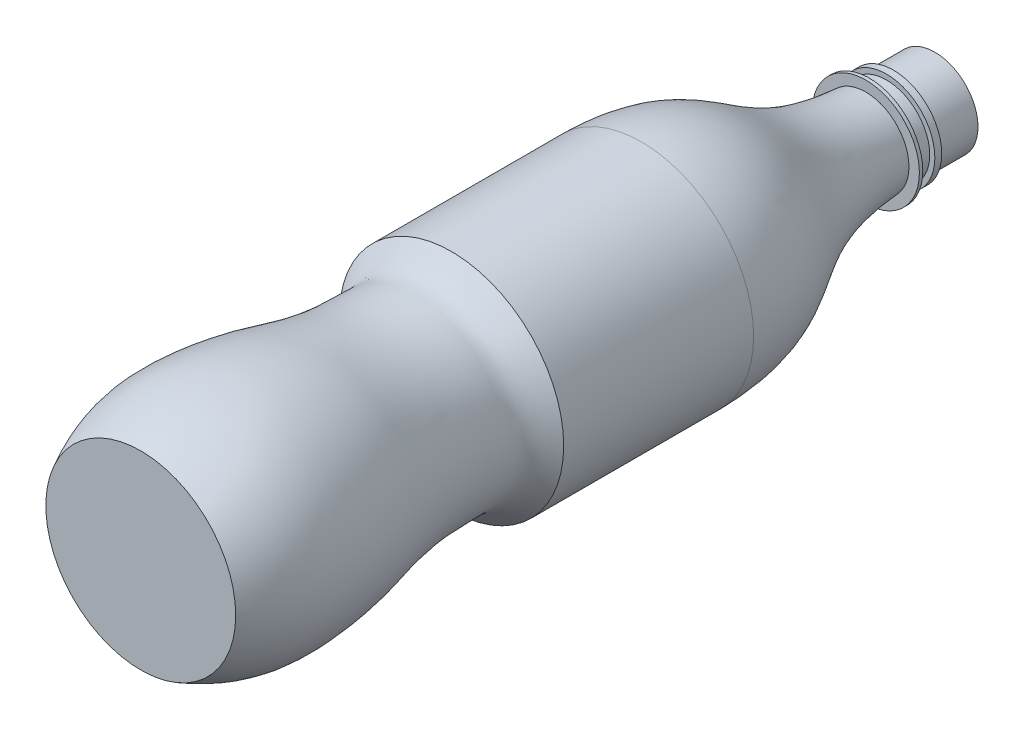
SolidWorks part; units mm, degrees
ref_plane "Front Plane" through (0, 0, 0) normal (0, 0, 1) x (1, 0, 0)
ref_plane "Top Plane" through (0, 0, 0) normal (0, 1, 0) x (1, 0, 0)
ref_plane "Right Plane" through (0, 0, 0) normal (1, 0, 0) x (0, 0, -1)
sketch "Sketch1" plane through (0, 0, 0) normal (0, 1, 0) x (1, 0, 0)
  line L0 (0, 0) -> (0, 230)
  line L5 (12.5, 218) -> (14, 218)
  line L6 (14, 218) -> (13.9999, 216)
  line L7 (0, 230) -> (12.5, 230)
  line L8 (12.5, 230) -> (12.5, 218)
  line L12 (12.5156, 216) -> (12.5, 210.9885)
  line L13 (12.5, 210.9885) -> (15.5, 210.9999)
  line L14 (15.5, 210.9999) -> (15.5156, 210)
  line L15 (15.5156, 210) -> (12.5, 210)
  line L16 (32.5, 145) -> (32.5, 90)
  line L17 (15.5156, 210) -> (62.3234, 210)
  line L19 (27.5, 0) -> (0, 0)
  line L20 (13.9999, 216) -> (12.5156, 216)
  spline S0 degree 3 poles (12.5, 210) (14.9221, 175.1275) (31.9793, 179.5644) (32.5, 145) knots 0 0 0 0 1 1 1 1
  spline S1 degree 3 poles (32.5, 90) (25.7218, 83.3162) (26.9365, 82.4142) (26.81, 66.9977) (28.4682, 57.1312) (32.0963, 44.0108) (34.9879, 23.7762) (33.2149, 10.7399) (27.5, 0) knots 0 0 0 0 0.249131 0.300006 0.485552 0.527189 0.69319 1 1 1 1
  point P1 (25, 64.3825)
  point P3 (33.6503, 30)
  point P4 (32.5, 35.8184)
  point P20 (0, 0)
  point P22 (0, 0)
  point P24 (0, 218)
  point P25 (0, 0)
  point P26 (0.3671, -0.2439)
  point P27 (30.4351, 50)
  point P28 (0, 0)
  dimension "D2" = 32.5
  dimension "D3" = 230
  dimension "D4" = 210
  dimension "D5" = 12
  dimension "D6" = 1
  dimension "D7" = 2
  dimension "D8" = 12.5
  dimension "D9" = 3
  dimension "D10" = 1.5
  dimension "D11" = 145
  dimension "D12" = 90
  dimension "D13" = 27.5
  dimension "D14" = 25
  dimension "D15" = 32.5
  dimension "D16" = 30
  dimension "D17" = 50
other "AlignGroup1"
revolve "Revolve3" add sketch "Sketch1" angle 360 about L0
